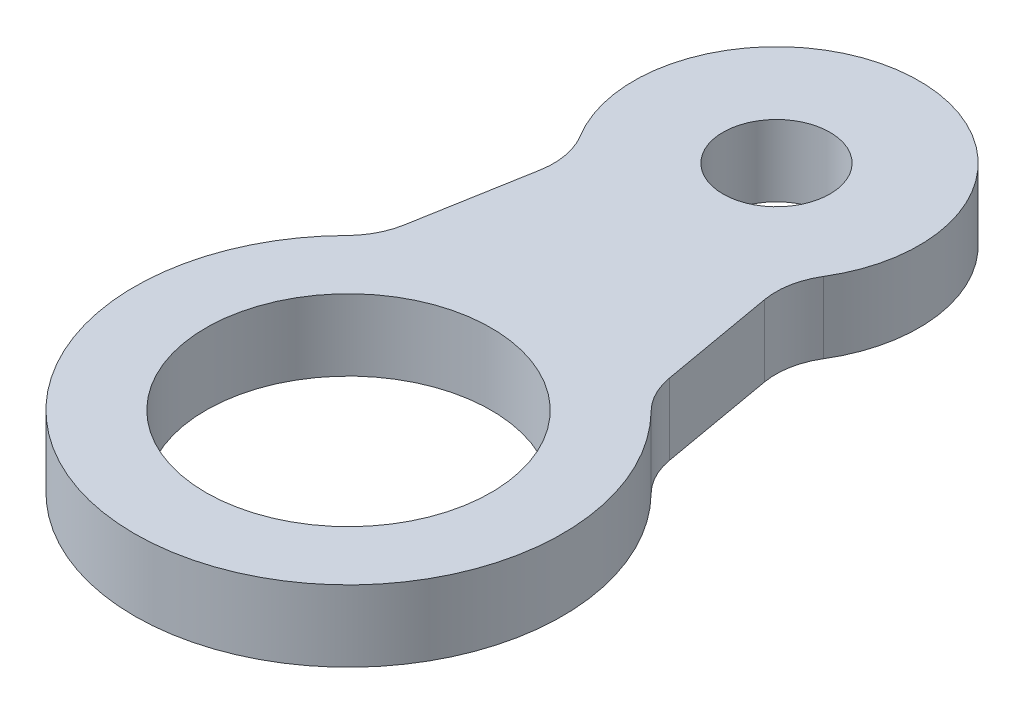
SolidWorks part; units mm, degrees
ref_plane "Front Plane" through (0, 0, 0) normal (0, 0, 1) x (1, 0, 0)
ref_plane "Top Plane" through (0, 0, 0) normal (0, 1, 0) x (1, 0, 0)
ref_plane "Right Plane" through (0, 0, 0) normal (1, 0, 0) x (0, 0, -1)
sketch "Sketch1" plane through (0, 0, 0) normal (0, 1, 0) x (1, 0, 0)
  line L0 (0, 0) -> (0, 76.2) construction
  line L5 (-24.3579, 29.2968) -> (-19.05, 59.3995)
  line L6 (24.3579, 29.2968) -> (19.05, 59.3995)
  arc A0 (-24.3579, 29.2968) -> (24.3579, 29.2968) centre (0, 0) ccw
  circle A1 centre (0, 0) radius 25.4
  arc A2 (19.05, 59.3995) -> (-19.05, 59.3995) centre (0, 76.2) ccw
  circle A3 centre (0, 76.2) radius 9.525
  dimension "D1" = 25.4
  dimension "D2" = 38.1
  dimension "D6" = 19.05
  dimension "D7" = 12.7
  dimension "D3" = 10
  dimension "D4" = 38.1
  dimension "D5" = 76.2
extrude "Boss-Extrude1" add sketch "Sketch1" along normal blind 12.7
fillet "Fillet1" radius 12.7 4 edges at (19.05, 6.35, -59.3995) (-24.3579, 6.35, -29.2968) (-19.05, 6.35, -59.3995) (24.3579, 6.35, -29.2968)
sketch "Sketch2" plane through (0, 12.7, 0) normal (0, 1, 0) x (1, 0, 0)
  line L0 (12.7, -35.921) -> (12.7, -50.8)
  line L1 (12.7, -50.8) -> (25.4, -50.8)
  line L2 (25.4, -50.8) -> (25.4, -63.5)
  line L3 (25.4, -63.5) -> (-25.4, -63.5)
  line L4 (0, 0) -> (0, -63.5) construction
  line L5 (-25.4, -50.8) -> (-25.4, -63.5)
  line L6 (-12.7, -50.8) -> (-25.4, -50.8)
  line L7 (-12.7, -35.921) -> (-12.7, -50.8)
  arc A0 (-27.091, 26.7897) -> (27.091, 26.7897) centre (0, 0) ccw construction
  arc A1 (-12.7, -35.921) -> (12.7, -35.921) centre (0, 0) ccw
  dimension "D1" = 12.7
  dimension "D2" = 63.5
  dimension "D3" = 25.4
  dimension "D4" = 12.7
ref_plane "Plane1" through (0, -20.32, 0) normal (0, 1, 0) x (1, 0, 0)
